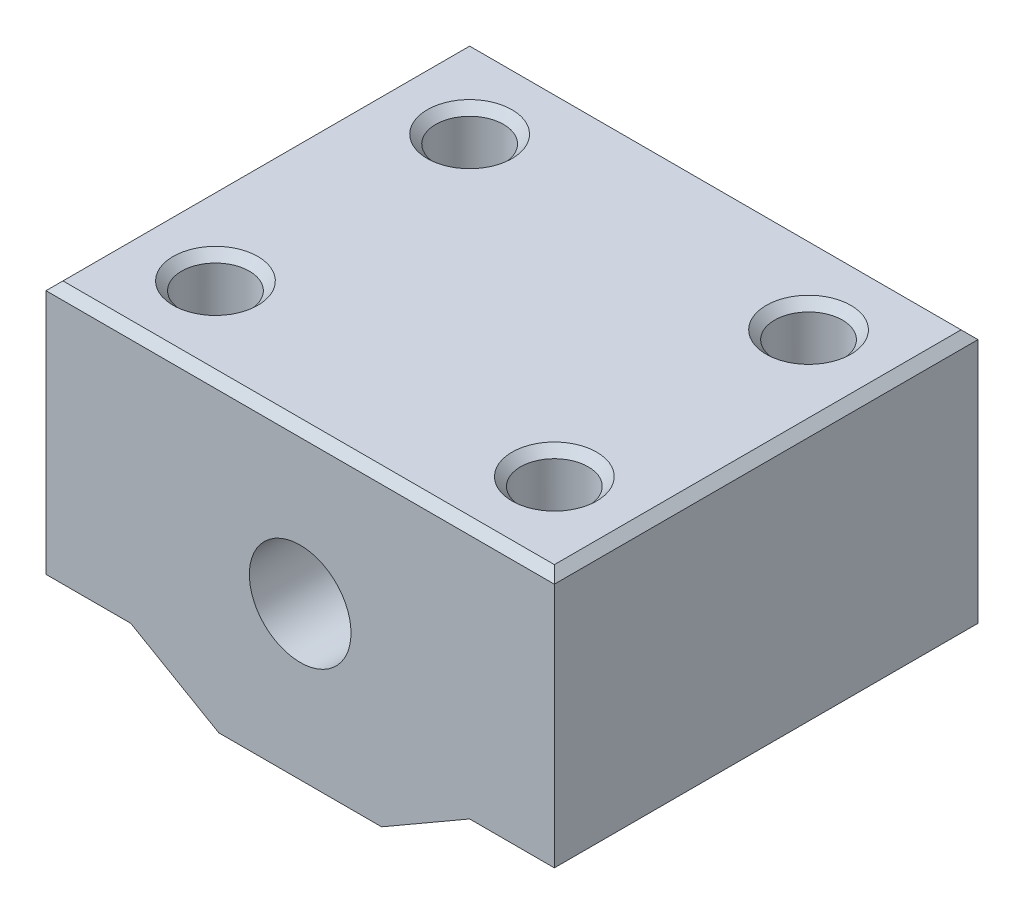
SolidWorks part; units mm, degrees
ref_plane "정면" through (0, 0, 0) normal (0, 0, 1) x (1, 0, 0)
ref_plane "윗면" through (0, 0, 0) normal (0, 1, 0) x (1, 0, 0)
ref_plane "우측면" through (0, 0, 0) normal (1, 0, 0) x (0, 0, -1)
sketch "스케치1" plane through (0, 0, 0) normal (0, 0, 1) x (1, 0, 0)
  line L0 (0, 7.5) -> (0, -7.5) construction
  line L1 (-15, -7.5) -> (-10, -7.5)
  line L2 (-15, -7.5) -> (-15, 7.5)
  line L3 (-15, 7.5) -> (15, 7.5)
  line L4 (15, -7.5) -> (15, 7.5)
  line L5 (-15, -7.5) -> (15, 7.5) construction
  line L6 (-15, 7.5) -> (15, -7.5) construction
  line L7 (-10, -7.5) -> (-4.8038, -10.5)
  line L8 (10, -7.5) -> (4.8038, -10.5)
  line L9 (-4.8038, -10.5) -> (4.8038, -10.5)
  line L10 (10, -7.5) -> (15, -7.5)
  point P0 (0, 0)
  point P13 (0, -10.5)
  dimension "D1" = 30
  dimension "D2" = 15
  dimension "D3" = 3
  dimension "D4" = 20
  dimension "D5" = 30
extrude "보스-돌출1" add sketch "스케치1" along normal blind 25
sketch "스케치2" plane through (0, 7.5, 0) normal (0, 1, 0) x (1, 0, 0)
  line L0 (0, 0) -> (0, -25) construction
  line L1 (-10, 0) -> (-10, -25) construction
  line L2 (10, 0) -> (10, -25) construction
  line L3 (-15, -12.5) -> (15, -12.5) construction
  line L4 (15, 0) -> (-15, 0)
  line L5 (-15, 0) -> (-15, -25)
  line L6 (-15, -25) -> (15, -25)
  line L7 (15, -25) -> (15, 0)
  line L8 (15, 0) -> (-15, 0)
  line L9 (-15, 0) -> (-15, -25)
  line L10 (-15, -25) -> (15, -25)
  line L11 (15, -25) -> (15, 0)
  circle A0 centre (-10, -5) radius 2
  circle A1 centre (10, -5) radius 2
  circle A2 centre (-10, -20) radius 2
  circle A3 centre (10, -20) radius 2
  point P20 (-10, -12.5)
  dimension "D2" = 4
  dimension "D3" = 15
  dimension "D4" = 5
  dimension "D1" = 0
extrude "컷-돌출1" cut sketch "스케치2" against normal through all contours A0 | A2 | A3 | A1
sketch "스케치3" plane through (0, 0, 25) normal (0, 0, 1) x (1, 0, 0)
  line L0 (0, 7.5) -> (0, -10.5) construction
  line L1 (15, 7.5) -> (-15, 7.5) construction
  line L2 (-4.8038, -10.5) -> (4.8038, -10.5) construction
  circle A0 centre (0, -1.5) radius 3
  dimension "D1" = 6
  dimension "D2" = 9
extrude "컷-돌출2" cut sketch "스케치3" against normal through all
chamfer "모따기1" distance 0.5 angle 45 8 edges at (15, 7.5, 12.5) (0, 7.5, 25) (-15, 7.5, 12.5) (0, 7.5, 0) (-10, 7.5, 7) (-10, 7.5, 22) (10, 7.5, 22) (10, 7.5, 7)
